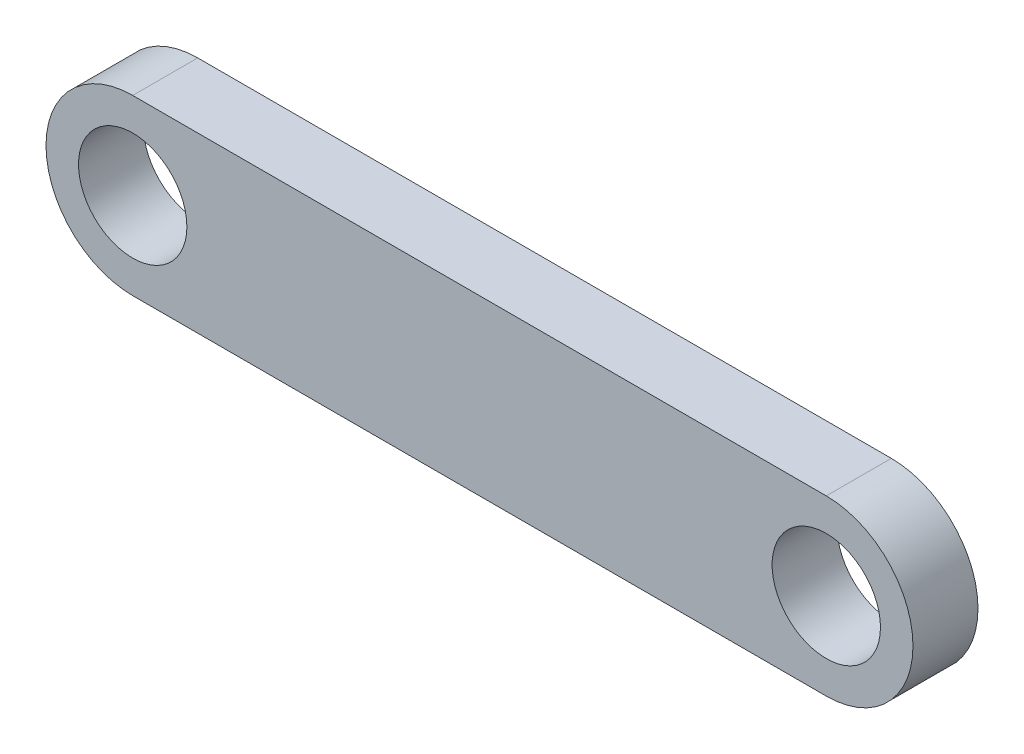
SolidWorks part; units mm, degrees
material "ABS"
ref_plane "Front Plane" through (0, 0, 0) normal (0, 0, 1) x (1, 0, 0)
ref_plane "Top Plane" through (0, 0, 0) normal (0, 1, 0) x (1, 0, 0)
ref_plane "Right Plane" through (0, 0, 0) normal (1, 0, 0) x (0, 0, -1)
sketch "Sketch1" plane through (0, 0, 0) normal (0, 0, 1) x (1, 0, 0)
  line L0 (0, 0) -> (-32, 0)
  dimension "D1" = 32
sketch "Sketch2" plane through (0, 0, 0) normal (0, 0, 1) x (1, 0, 0)
  line L0 (-32, 4) -> (0, 4)
  line L1 (-32, -4) -> (0, -4)
  circle A0 centre (-32, 0) radius 2.5
  circle A1 centre (0, 0) radius 2.5
  arc A2 (-32, 4) -> (-32, -4) centre (-32, 0) ccw
  arc A3 (0, -4) -> (0, 4) centre (0, 0) ccw
  dimension "D1" = 5
  dimension "D2" = 8
  dimension "D3" = 5
  dimension "D4" = 8
extrude "Boss-Extrude1" add sketch "Sketch2" along normal blind 3
